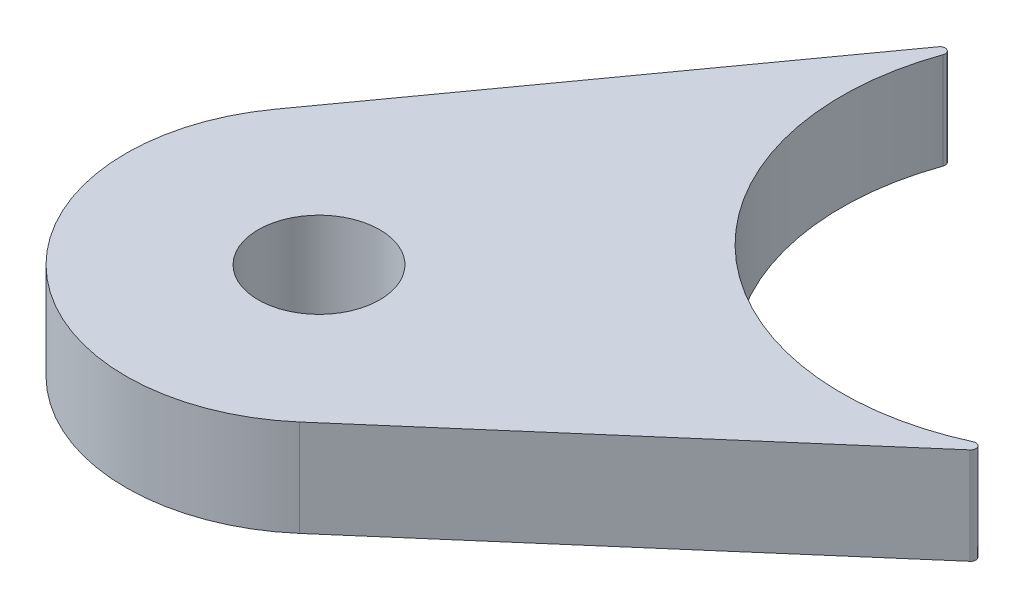
SolidWorks part; units mm, degrees
material "AISI 4130 Steel, annealed at 865C"
ref_plane "X-Y Datum" through (0, 0, 0) normal (0, 0, 1) x (1, 0, 0)
ref_plane "X-Z Datum" through (0, 0, 0) normal (0, 1, 0) x (1, 0, 0)
ref_plane "Y-Z Datum" through (0, 0, 0) normal (1, 0, 0) x (0, 0, -1)
sketch "Sketch1" plane through (0, 0, 0) normal (0, 1, 0) x (1, 0, 0)
  line L0 (-26.1126, -14.5455) -> (-10.3086, 7.4177)
  line L1 (-12.1475, -27.3107) -> (8.3115, -9.6026)
  arc A0 (-26.1126, -14.5455) -> (-12.1475, -27.3107) centre (-18.3811, -20.1088) ccw
  circle A2 centre (0, 0) radius 12.7 construction
  circle A3 centre (-18.3811, -20.1088) radius 9.525 construction
  arc A4 (-10.3086, 7.4177) -> (8.3115, -9.6026) centre (0, 0) ccw
  circle A5 centre (-18.3811, -20.1088) radius 3
  dimension "D3" = 25.4
  dimension "D4" = 19.05
  dimension "D5" = 6
  dimension "D1" = 27.2439
  dimension "D2" = 18.3811
extrude "Boss-Extrude1" add sketch "Sketch1" along normal blind 4.7625
fillet "Fillet1" radius 0.254 2 edges at (-10.3086, 2.3813, -7.4177) (8.3115, 2.3813, 9.6026)
